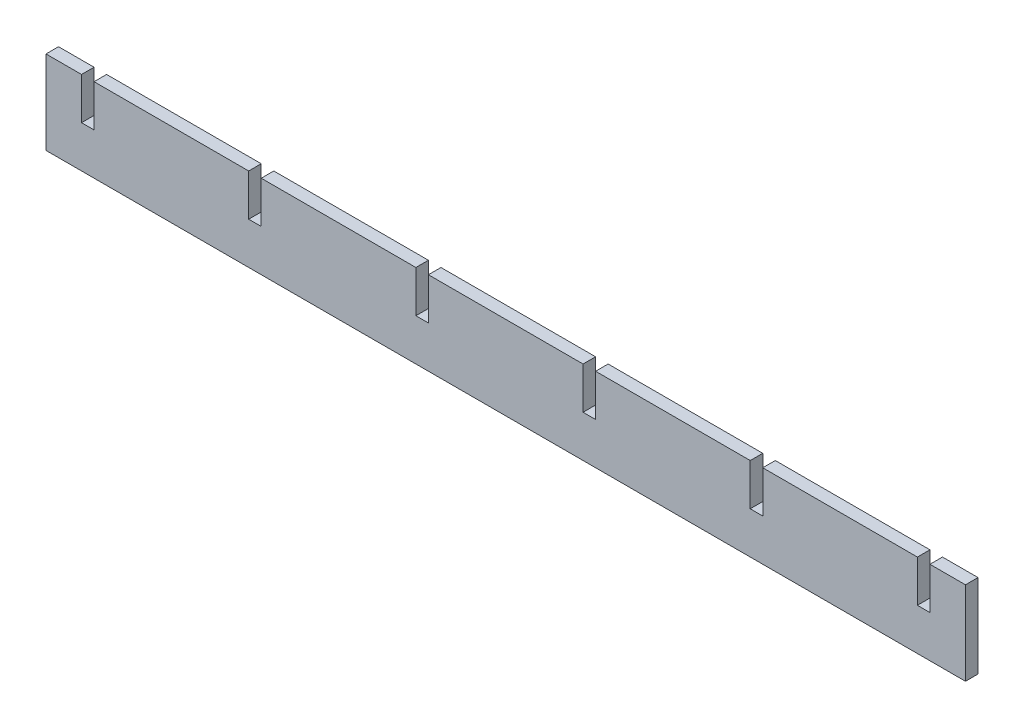
SolidWorks part; units mm, degrees
ref_plane "Front Plane" through (0, 0, 0) normal (0, 0, 1) x (1, 0, 0)
ref_plane "Top Plane" through (0, 0, 0) normal (0, 1, 0) x (1, 0, 0)
ref_plane "Right Plane" through (0, 0, 0) normal (1, 0, 0) x (0, 0, -1)
sketch "Sketch2" plane through (0, 0, 0) normal (0, 0, 1) x (1, 0, 0)
  line L1 (0, 0) -> (220, 0)
  line L2 (0, 0) -> (0, 20)
  line L3 (0, 20) -> (220, 20)
  line L4 (220, 0) -> (220, 20)
  dimension "D1" = 220
  dimension "D2" = 20
extrude "Boss-Extrude1" add sketch "Sketch2" along normal blind 3
sketch "Sketch4" plane through (0, 0, 0) normal (0, 0, 1) x (1, 0, 0)
  line L1 (220, 20) -> (0, 20) construction
  line L3 (8.5, 20) -> (11.5, 20)
  line L4 (8.5, 20) -> (8.5, 10)
  line L5 (8.5, 10) -> (11.5, 10)
  line L6 (11.5, 20) -> (11.5, 10)
  dimension "D2" = 3
  dimension "D3" = 10
extrude "Cut-Extrude2" cut sketch "Sketch4" along normal through all
pattern_linear "LPattern1" count 6 spacing 40 along (1, 0, 0) of "Cut-Extrude2"
